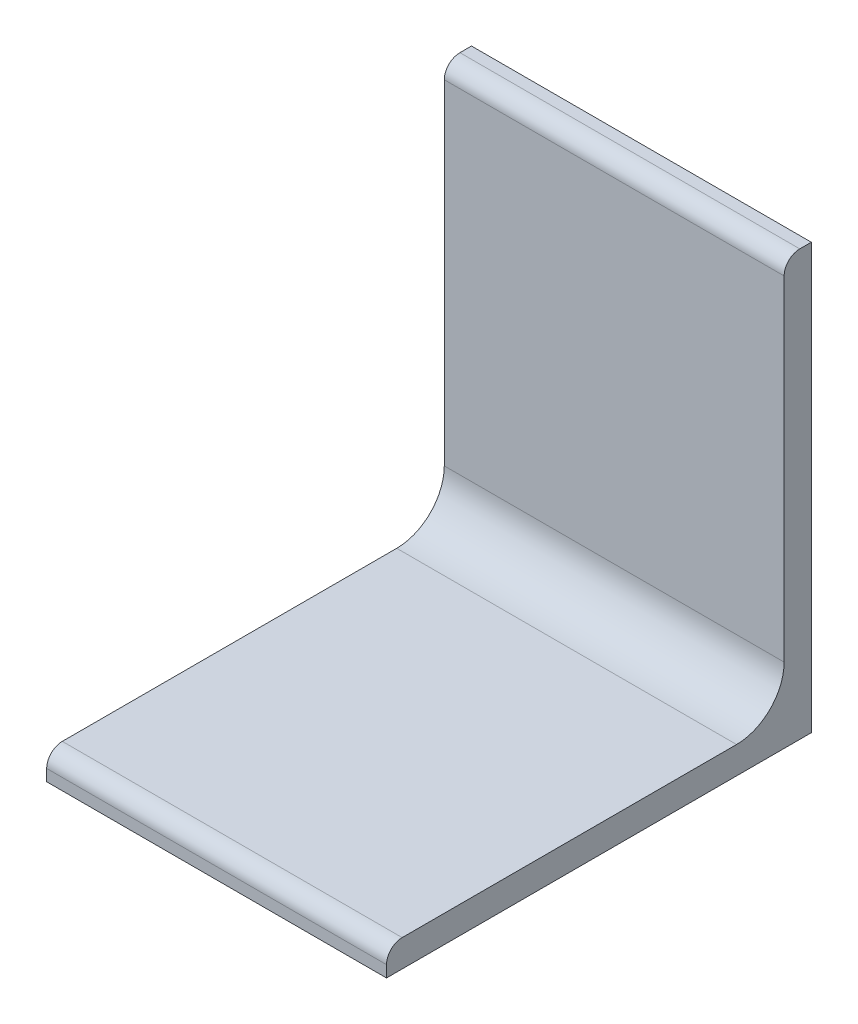
SolidWorks part; units mm, degrees
material "Простая углеродистая сталь"
ref_plane "Спереди" through (0, 0, 0) normal (0, 0, 1) x (1, 0, 0)
ref_plane "Сверху" through (0, 0, 0) normal (0, 1, 0) x (1, 0, 0)
ref_plane "Справа" through (0, 0, 0) normal (1, 0, 0) x (0, 0, -1)
sketch "Эскиз1" plane through (0, 0, 0) normal (0, 0, 1) x (1, 0, 0)
  line L0 (0, 0) -> (100, 0)
  dimension "D1" = 100
other "Уголки гост 8509-86 125Х125Х8(1)"
ref_plane "Плоскость1" through (0, 0, 0) normal (1, 0, 0) x (0, 1, 0)
sketch "Sketch11" plane through (0, 0, 0) normal (1, 0, 0) x (0, 1, 0)
  line L0 (-33.6, -33.6) -> (-33.6, 91.4)
  line L1 (91.4, -33.6) -> (91.4, -30.2)
  line L2 (-25.6, 86.8) -> (-25.6, -11.6)
  line L3 (-11.6, -25.6) -> (86.8, -25.6)
  line L4 (-33.6, 91.4) -> (-30.2, 91.4)
  line L5 (91.4, -33.6) -> (-33.6, -33.6)
  line L6 (0, 0) -> (0, -33.6) construction
  line L8 (0, 0) -> (91.4, 0) construction
  line L9 (0, 0) -> (0, 91.4) construction
  line L10 (0, 0) -> (-33.6, 0) construction
  arc A0 (86.8, -25.6) -> (91.4, -30.2) centre (86.8, -30.2) cw
  arc A1 (-25.6, 86.8) -> (-30.2, 91.4) centre (-30.2, 86.8) ccw
  arc A2 (-11.6, -25.6) -> (-25.6, -11.6) centre (-11.6, -11.6) cw
  point P14 (0, 0)
  point P15 (0, 0)
  point P16 (91.4, -33.6)
  point P21 (-33.6, -33.6)
  dimension "R1" = 14
  dimension "R2" = 4.6
  dimension "t" = 8
